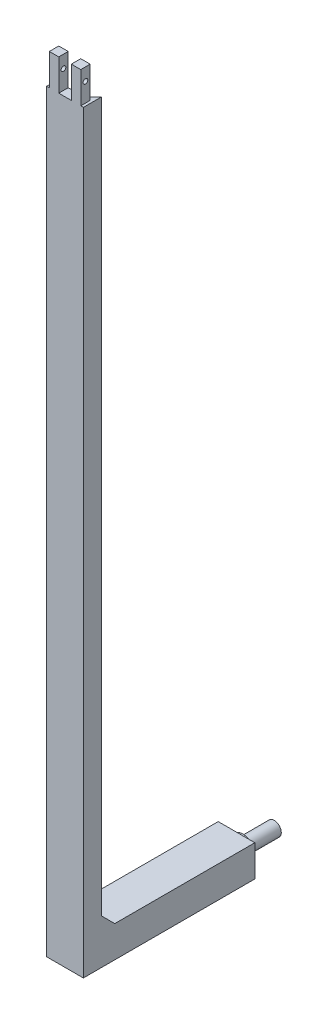
SolidWorks part; units mm, degrees
ref_plane "Front Plane" through (0, 0, 0) normal (0, 0, 1) x (1, 0, 0)
ref_plane "Top Plane" through (0, 0, 0) normal (0, 1, 0) x (1, 0, 0)
ref_plane "Right Plane" through (0, 0, 0) normal (1, 0, 0) x (0, 0, -1)
sketch "Sketch2" plane through (0, 0, 0) normal (0, 0, 1) x (1, 0, 0)
  line L1 (0, 0) -> (-6, 0)
  line L2 (0, 0) -> (0, -240)
  line L3 (0, -240) -> (-6, -240)
  line L4 (-6, 0) -> (-6, -240)
  dimension "D1" = 6
  dimension "D2" = 240
extrude "Boss-Extrude1" add sketch "Sketch2" along normal blind 3
sketch "Sketch4" plane through (0, -240, 0) normal (0, -1, 0) x (-1, 0, 0)
  line L0 (0, 0) -> (-2.8284, 2.8284)
  line L1 (-2.8284, 2.8284) -> (-2.8284, -3)
  line L2 (-2.8284, -3) -> (0, -3)
  line L3 (0, -3) -> (0, 0)
  line L4 (3, 0) -> (3, -3.7119) construction
  line L5 (6, 0) -> (0, 0) construction
  line L6 (8.8284, -3) -> (6, -3)
  line L7 (8.8284, 2.8284) -> (8.8284, -3)
  line L8 (6, 0) -> (8.8284, 2.8284)
  line L9 (6, -3) -> (6, 0)
  dimension "D1" = 135
  dimension "D2" = 4
extrude "Boss-Extrude2" add sketch "Sketch4" against normal up to vertex (240 mm away)
sketch "Sketch5" plane through (0, 0, 0) normal (0, 1, 0) x (1, 0, 0)
  line L0 (2.8284, -3) -> (-8.8284, -3) construction
  line L1 (-8, -3) -> (-5, -3)
  line L2 (-8, -3) -> (-8, 0)
  line L3 (-8, 0) -> (-5, 0)
  line L4 (-5, -3) -> (-5, 0)
  line L5 (-3, 0) -> (-3, -4.0355) construction
  line L6 (0, 0) -> (-6, 0) construction
  line L7 (2, 0) -> (-1, 0)
  line L8 (-1, -3) -> (-1, 0)
  line L9 (2, -3) -> (-1, -3)
  line L10 (2, -3) -> (2, 0)
  dimension "D1" = 3
  dimension "D2" = 2
  dimension "D3" = 0
extrude "Boss-Extrude3" add sketch "Sketch5" along normal blind 10
sketch "Sketch6" plane through (2, 0, 0) normal (1, 0, 0) x (0, 0, -1)
  line L0 (-3, 10) -> (-3, 0) construction
  line L1 (-3, 10) -> (0, 10) construction
  circle A0 centre (-1.5, 6) radius 0.75
  dimension "D1" = 1.5
  dimension "D2" = 1.5
  dimension "D3" = 4
extrude "Cut-Extrude1" cut sketch "Sketch6" against normal blind 40
sketch "Sketch7" plane through (0, 0, 0) normal (0, 0, -1) x (-1, 0, 0)
  line L0 (-2.8284, 0) -> (-2.8284, -240) construction
  line L1 (8.8284, -240) -> (-2.8284, -240)
  line L2 (8.8284, -240) -> (8.8284, -230)
  line L3 (8.8284, -230) -> (-2.8284, -230)
  line L4 (-2.8284, -240) -> (-2.8284, -230)
  dimension "D1" = 10
extrude "Boss-Extrude4" add sketch "Sketch7" along normal blind 51.58
sketch "Sketch8" plane through (0, 0, -51.58) normal (0, 0, -1) x (-1, 0, 0)
  line L0 (-2.8284, -240) -> (8.8284, -240) construction
  line L1 (-2.8284, -230) -> (-2.8284, -240) construction
  circle A0 centre (3, -235) radius 2.25
  point P4 (3, -240)
  point P7 (-2.8284, -235)
  dimension "D1" = 0
  dimension "D2" = 0
  dimension "D3" = 4.5
extrude "Boss-Extrude5" add sketch "Sketch8" along normal blind 12
sketch "Sketch9" plane through (-8.8284, 0, 0) normal (-1, 0, 0) x (0, 0, 1)
  line L0 (-7, -230) -> (0, -230)
  line L1 (-51.58, -230) -> (-2.8284, -230) construction
  line L2 (0, -230) -> (0, -223)
  line L3 (0, -223) -> (-7, -230)
  dimension "D1" = 7
  dimension "D2" = 7
extrude "Boss-Extrude6" add sketch "Sketch9" against normal up to vertex (11.6569 mm away) up to point (2.8284, -230, -2.8284)
sketch "Sketch10" plane through (0, 0, -51.58) normal (0, 0, -1) x (-1, 0, 0)
  circle A0 centre (3, -235) radius 3.5
  dimension "D1" = 7
extrude "Boss-Extrude7" add sketch "Sketch10" along normal blind 2
